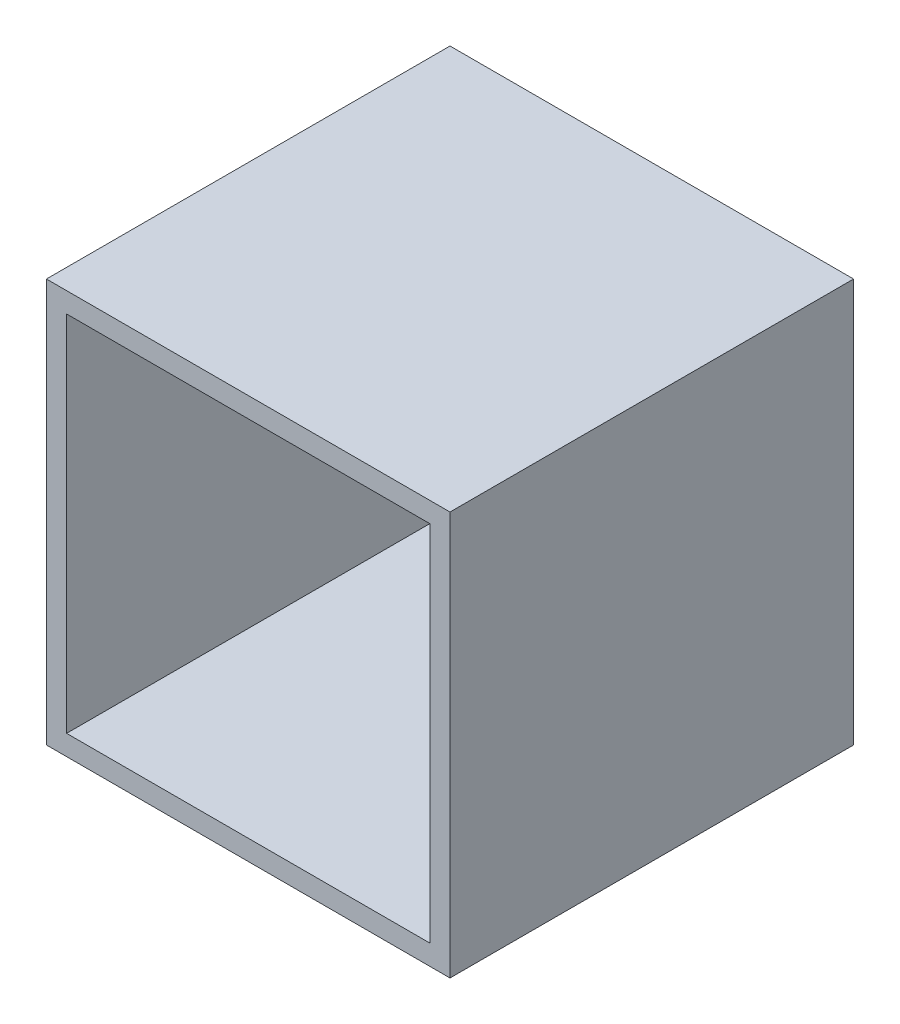
SolidWorks part; units mm, degrees
ref_plane "Front Plane" through (0, 0, 0) normal (0, 0, 1) x (1, 0, 0)
ref_plane "Top Plane" through (0, 0, 0) normal (0, 1, 0) x (1, 0, 0)
ref_plane "Right Plane" through (0, 0, 0) normal (1, 0, 0) x (0, 0, -1)
sketch "Sketch2" plane through (0, 0, 0) normal (0, 0, 1) x (1, 0, 0)
  line L1 (-48.1313, 27.2727) -> (51.8687, 27.2727)
  line L2 (-48.1313, 27.2727) -> (-48.1313, -72.7273)
  line L3 (-48.1313, -72.7273) -> (51.8687, -72.7273)
  line L4 (51.8687, 27.2727) -> (51.8687, -72.7273)
  dimension "D1" = 100
  dimension "D2" = 100
extrude "Boss-Extrude1" add sketch "Sketch2" along normal blind 100 contours L1 L4 L3 L2
shell "Shell2" thickness 5
